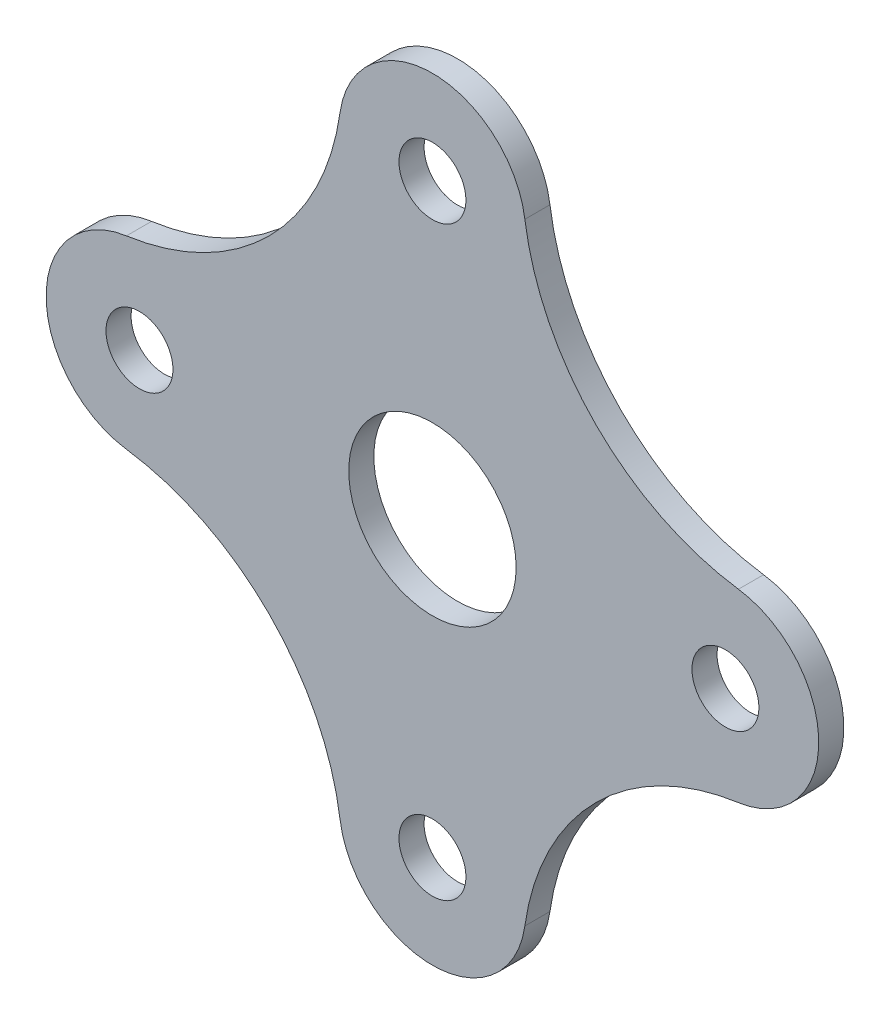
SolidWorks part; units mm, degrees
material "AISI 1020"
ref_plane "Front Plane" through (0, 0, 0) normal (0, 0, 1) x (1, 0, 0)
ref_plane "Top Plane" through (0, 0, 0) normal (0, 1, 0) x (1, 0, 0)
ref_plane "Right Plane" through (0, 0, 0) normal (1, 0, 0) x (0, 0, -1)
sketch "Sketch1" plane through (0, 0, 0) normal (0, 0, 1) x (1, 0, 0)
  line L0 (0, -35) -> (0, 35) construction
  line L1 (-11.1496, -35) -> (-11.1496, -11.1496)
  line L2 (11.1496, -35) -> (11.1496, -11.1496)
  line L3 (-35, 0) -> (35, 0) construction
  line L4 (-35, 11.1496) -> (-11.1496, 11.1496)
  line L5 (-35, -11.1496) -> (-11.1496, -11.1496)
  line L6 (11.1496, 11.1496) -> (35, 11.1496)
  line L7 (11.1496, 11.1496) -> (11.1496, 35)
  line L8 (-11.1496, 11.1496) -> (-11.1496, 35)
  line L9 (11.1496, -11.1496) -> (35, -11.1496)
  arc A0 (-11.1496, -35) -> (11.1496, -35) centre (0, -35) ccw
  arc A1 (11.1496, 35) -> (-11.1496, 35) centre (0, 35) ccw
  arc A2 (-35, 11.1496) -> (-35, -11.1496) centre (-35, 0) ccw
  arc A3 (35, -11.1496) -> (35, 11.1496) centre (35, 0) ccw
  circle A4 centre (-35, 0) radius 4
  circle A5 centre (35, 0) radius 4
  circle A6 centre (0, 35) radius 4
  circle A7 centre (0, -35) radius 4
  circle A8 centre (0, 0) radius 10
  point P2 (0, 0)
  point P9 (0, 0)
  dimension "D1" = 8
  dimension "D2" = 70
  dimension "D3" = 20
extrude "Boss-Extrude1" add sketch "Sketch1" along normal blind 3
fillet "Fillet1" radius 30 4 edges at (-11.1496, 11.1496, 1.5) (11.1496, 11.1496, 1.5) (11.1496, -11.1496, 1.5) (-11.1496, -11.1496, 1.5)
